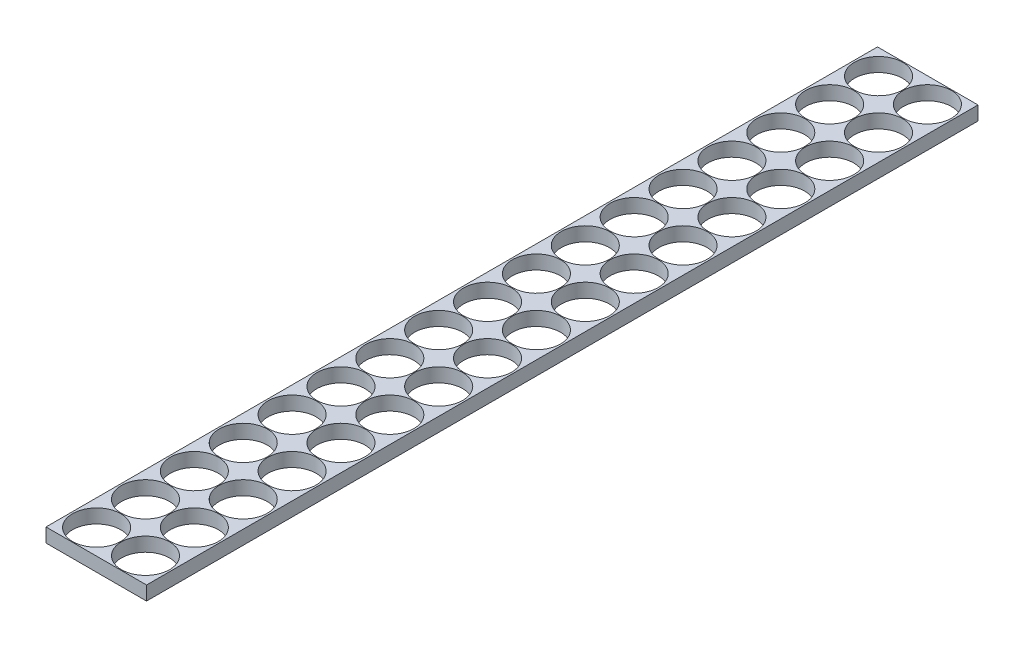
SolidWorks part; units mm, degrees
ref_plane "Front Plane" through (0, 0, 0) normal (0, 0, 1) x (1, 0, 0)
ref_plane "Top Plane" through (0, 0, 0) normal (0, 1, 0) x (1, 0, 0)
ref_plane "Right Plane" through (0, 0, 0) normal (1, 0, 0) x (0, 0, -1)
sketch "Sketch1" plane through (0, 0, 0) normal (0, 1, 0) x (1, 0, 0)
  line L0 (3.6, -59.55) -> (3.6, 0)
  line L1 (0, 0) -> (7.2, 0)
  line L2 (0, 0) -> (0, -59.55)
  line L3 (0, -59.55) -> (7.2, -59.55)
  line L4 (7.2, 0) -> (7.2, -59.55)
  line L5 (1.85, 0) -> (1.85, -59.55)
  line L6 (5.35, 0) -> (5.35, -59.55)
  circle A0 centre (1.85, -1.775) radius 1.725
  circle A1 centre (5.35, -1.775) radius 1.725
  circle A2 centre (1.85, -5.275) radius 1.725
  circle A3 centre (5.35, -5.275) radius 1.725
  circle A4 centre (1.85, -8.775) radius 1.725
  circle A5 centre (5.35, -8.775) radius 1.725
  circle A6 centre (1.85, -12.275) radius 1.725
  circle A7 centre (5.35, -12.275) radius 1.725
  circle A8 centre (1.85, -15.775) radius 1.725
  circle A9 centre (5.35, -15.775) radius 1.725
  circle A10 centre (1.85, -19.275) radius 1.725
  circle A11 centre (5.35, -19.275) radius 1.725
  circle A12 centre (1.85, -22.775) radius 1.725
  circle A13 centre (5.35, -22.775) radius 1.725
  circle A14 centre (1.85, -26.275) radius 1.725
  circle A15 centre (5.35, -26.275) radius 1.725
  circle A16 centre (1.85, -29.775) radius 1.725
  circle A17 centre (5.35, -29.775) radius 1.725
  circle A18 centre (1.85, -33.275) radius 1.725
  circle A19 centre (5.35, -33.275) radius 1.725
  circle A20 centre (1.85, -36.775) radius 1.725
  circle A21 centre (5.35, -36.775) radius 1.725
  circle A22 centre (1.85, -40.275) radius 1.725
  circle A23 centre (5.35, -40.275) radius 1.725
  circle A24 centre (1.85, -43.775) radius 1.725
  circle A25 centre (5.35, -43.775) radius 1.725
  circle A26 centre (1.85, -47.275) radius 1.725
  circle A27 centre (5.35, -47.275) radius 1.725
  circle A28 centre (1.85, -50.775) radius 1.725
  circle A29 centre (5.35, -50.775) radius 1.725
  circle A30 centre (1.85, -54.275) radius 1.725
  circle A31 centre (5.35, -54.275) radius 1.725
  circle A32 centre (1.85, -57.775) radius 1.725
  circle A33 centre (5.35, -57.775) radius 1.725
  dimension "D9" = 3.45
  dimension "D10" = 3.45
  dimension "D6" = 3.5
  dimension "D5" = 1.775
  dimension "D1" = 59.55
  dimension "D2" = 7.2
  dimension "D3" = 3.6
  dimension "D4" = 3.5
  dimension "D12" = 17
extrude "Boss-Extrude1" add sketch "Sketch1" along normal blind 1 contours A32 L5 L3 L0 L1 A0 A2 A4 A6 A8 A10 A12 A14 A16 A18 A20 A22 A24 A26 A28 A30 | A32 L5 A30 A28 A26 A24 A22 A20 A18 A16 A14 A12 A10 A8 A6 A4 A2 A0 L1 L2 L3 | A33 L6 L3 L4 L1 A1 A3 A5 A7 A9 A11 A13 A15 A17 A19 A21 A23 A25 A27 A29 A31 | A33 L6 A31 A29 A27 A25 A23 A21 A19 A17 A15 A13 A11 A9 A7 A5 A3 A1 L1 L0 L3
